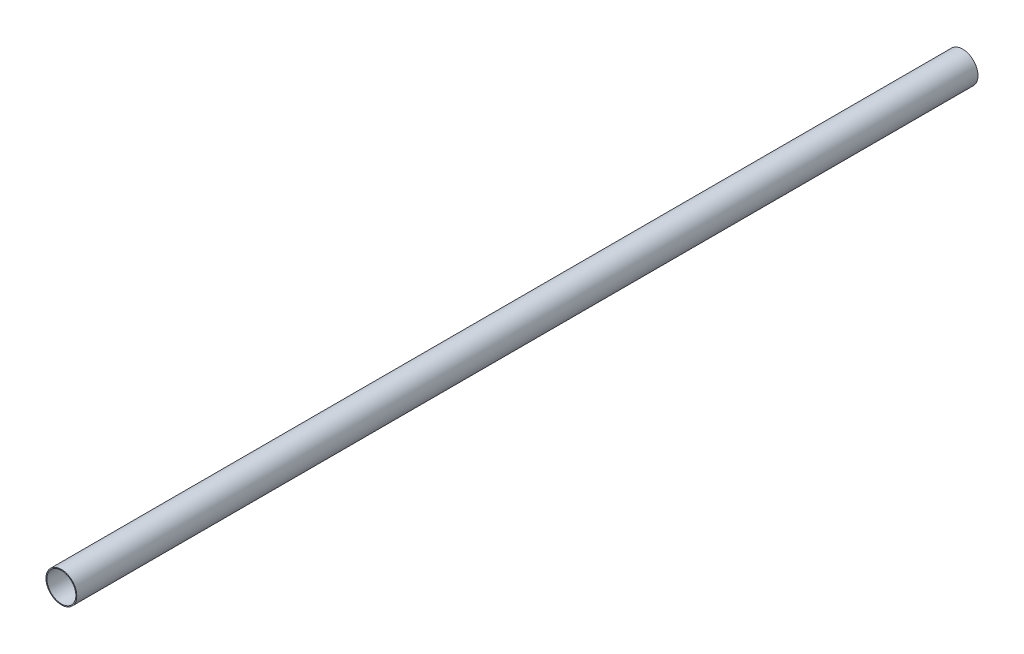
SolidWorks part; units mm, degrees
ref_plane "Front Plane" through (0, 0, 0) normal (0, 0, 1) x (1, 0, 0)
ref_plane "Top Plane" through (0, 0, 0) normal (0, 1, 0) x (1, 0, 0)
ref_plane "Right Plane" through (0, 0, 0) normal (1, 0, 0) x (0, 0, -1)
sketch "Sketch1" plane through (0, 0, 0) normal (0, 0, 1) x (1, 0, 0)
  circle A0 centre (8757.1269, 3099.8726) radius 11.43
  circle A1 centre (8757.1269, 3099.8726) radius 12.1539
extrude "Boss-Extrude1" add sketch "Sketch1" along normal blind 711.2
